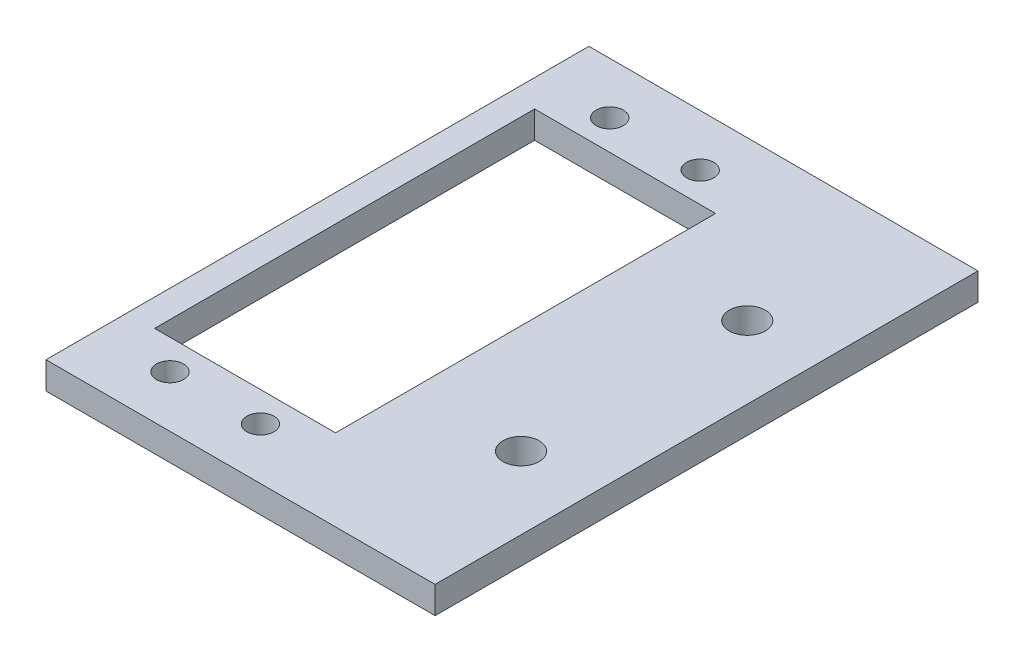
SolidWorks part; units mm, degrees
ref_plane "前视基准面" through (0, 0, 0) normal (0, 0, 1) x (1, 0, 0)
ref_plane "上视基准面" through (0, 0, 0) normal (0, 1, 0) x (1, 0, 0)
ref_plane "右视基准面" through (0, 0, 0) normal (1, 0, 0) x (0, 0, -1)
sketch "草图1" plane through (0, 0, 0) normal (0, 1, 0) x (1, 0, 0)
  line L0 (0, 0) -> (0, -60)
  line L1 (0, -60) -> (43, -60)
  line L2 (43, -60) -> (43, 0)
  line L3 (43, 0) -> (0, 0)
  line L4 (0, -30) -> (43, -30) construction
  line L5 (8, -5.7) -> (18, -5.7) construction
  line L6 (13, -5.7) -> (13, -30) construction
  line L8 (3, -9) -> (23, -9)
  line L9 (3, -9) -> (3, -51)
  line L10 (3, -51) -> (23, -51)
  line L11 (23, -9) -> (23, -51)
  line L12 (3, -9) -> (23, -51) construction
  line L13 (3, -51) -> (23, -9) construction
  circle A0 centre (8, -5.7) radius 1.5
  circle A1 centre (18, -5.7) radius 1.5
  circle A2 centre (8, -54.3) radius 1.5
  circle A3 centre (18, -54.3) radius 1.5
  circle A4 centre (35, -17.5) radius 2
  circle A5 centre (35, -42.5) radius 2
  point P25 (0, 0)
  point P26 (0, 0)
  dimension "D3" = 3
  dimension "D8" = 4
  dimension "D1" = 60
  dimension "D2" = 8
  dimension "D4" = 48.6
  dimension "10" = 10
  dimension "D5" = 8
  dimension "D6" = 20
  dimension "D7" = 42
  dimension "D9" = 25
  dimension "D10" = 12
  dimension "D11" = 43
extrude "凸台-拉伸1" add sketch "草图1" along normal blind 3
